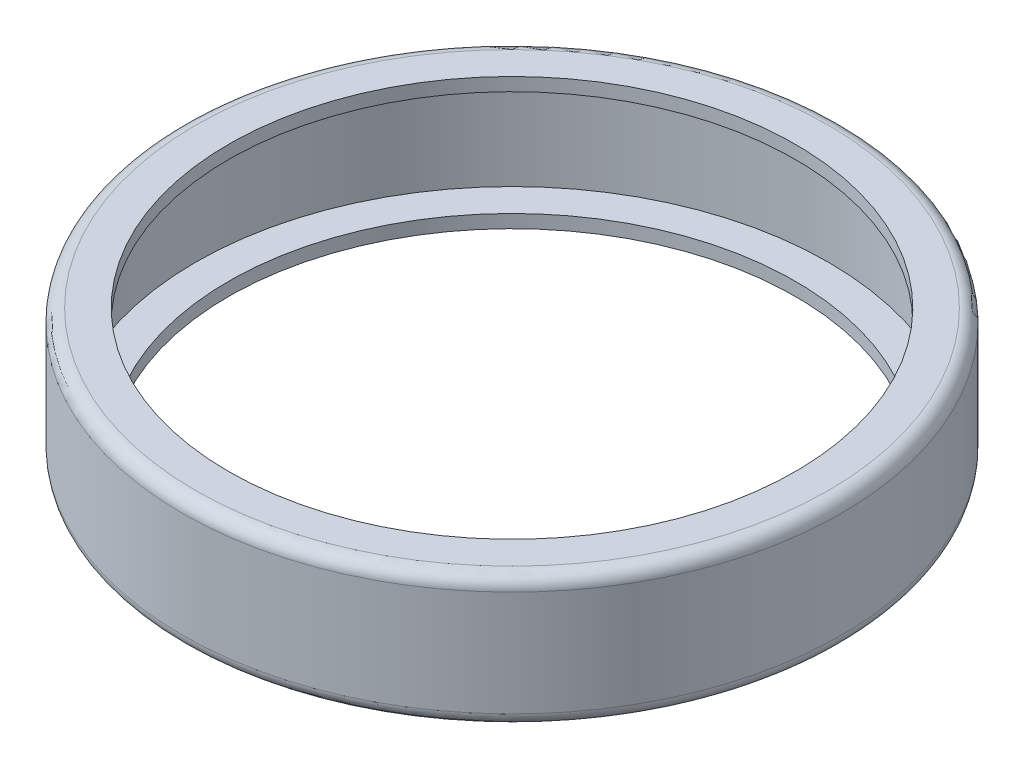
SolidWorks part; units mm, degrees
ref_plane "Front Plane" through (0, 0, 0) normal (0, 0, 1) x (1, 0, 0)
ref_plane "Top Plane" through (0, 0, 0) normal (0, 1, 0) x (1, 0, 0)
ref_plane "Right Plane" through (0, 0, 0) normal (1, 0, 0) x (0, 0, -1)
sketch "Sketch1" plane through (0, 0, 0) normal (0, 0, 1) x (1, 0, 0)
  line L0 (0, 9.0851) -> (0, 0) construction
  line L1 (0, 0) -> (-21.5, 0) construction
  line L2 (-21.5, 0) -> (-25, 0)
  line L3 (-25, 0) -> (-25, 10)
  line L4 (-25, 10) -> (-21.5, 10)
  line L5 (-21.5, 10) -> (-21.5, 9)
  line L6 (-21.5, 9) -> (-24, 9)
  line L7 (-24, 9) -> (-24, 1)
  line L8 (-24, 1) -> (-21.5, 1)
  line L9 (-21.5, 1) -> (-21.5, 0)
  dimension "D1" = 10
  dimension "D2" = 3.5
  dimension "D3" = 1
  dimension "D4" = 1
  dimension "D5" = 25
revolve "Revolve1" add sketch "Sketch1" angle 360 about L0
fillet "Fillet1" radius 1 2 edges at (0, 0, 25) (0, 10, 25)
